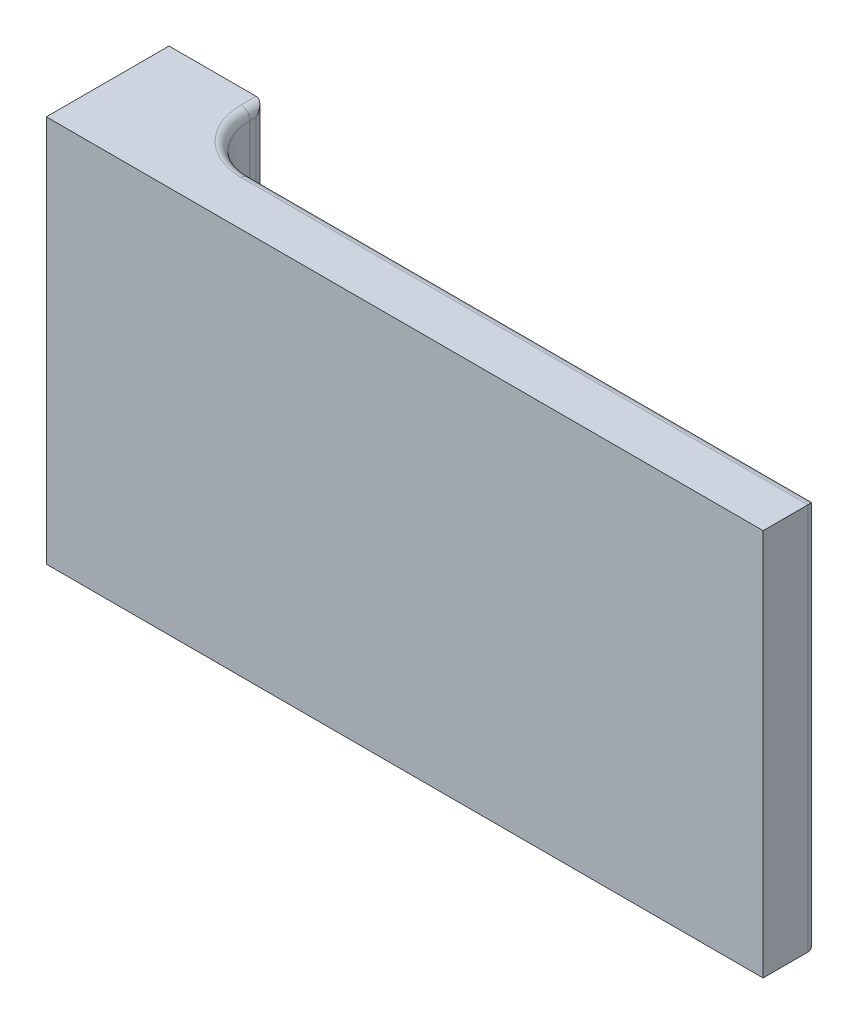
SolidWorks part; units mm, degrees
ref_plane "Front Plane" through (0, 0, 0) normal (0, 0, 1) x (1, 0, 0)
ref_plane "Top Plane" through (0, 0, 0) normal (0, 1, 0) x (1, 0, 0)
ref_plane "Right Plane" through (0, 0, 0) normal (1, 0, 0) x (0, 0, -1)
sketch "Sketch1" plane through (0, 0, 0) normal (0, 0, 1) x (1, 0, 0)
  line L0 (-9.2306, -8.7723) -> (-9.2306, -19.5725) construction
  line L1 (-9.2306, -8.7723) -> (-29.2123, -8.7723)
  line L2 (-9.2306, -8.7723) -> (-9.2306, -19.5725)
  line L3 (-9.2306, -19.5725) -> (-29.2123, -19.5725)
  line L4 (-29.2123, -8.7723) -> (-29.2123, -19.5725)
extrude "Boss-Extrude1" add sketch "Sketch1" against normal up to vertex (1.5 mm away)
sketch "Sketch3" plane through (0, 0, -1.5) normal (0, 0, -1) x (-1, 0, 0)
  line L0 (26.2828, -14.8612) -> (29.2123, -14.8612) construction
  line L1 (29.2123, -8.7723) -> (26.5343, -8.7723)
  line L2 (29.2123, -8.7723) -> (29.2123, -14.8612)
  line L3 (29.2123, -14.8612) -> (26.5343, -14.8612)
  line L4 (26.5343, -8.7723) -> (26.5343, -14.8612)
extrude "Boss-Extrude2" add sketch "Sketch3" along normal offset from surface (1.92 mm away) 0.2
fillet "Fillet1" radius 1.5 1 edges at (-26.5343, -11.8168, -1.5)
fillet "Fillet2" radius 0.25 8 edges at (-26.5343, -14.8612, -3.21) (-26.5343, -8.7723, -3.21) (-26.0949, -8.7723, -1.9393) (-26.0949, -14.8612, -1.9393) (-26.5343, -11.8168, -3.42) (-19.2214, -19.5725, -1.5) (-9.2306, -14.1724, -1.5) (-17.1324, -8.7723, -1.5)
